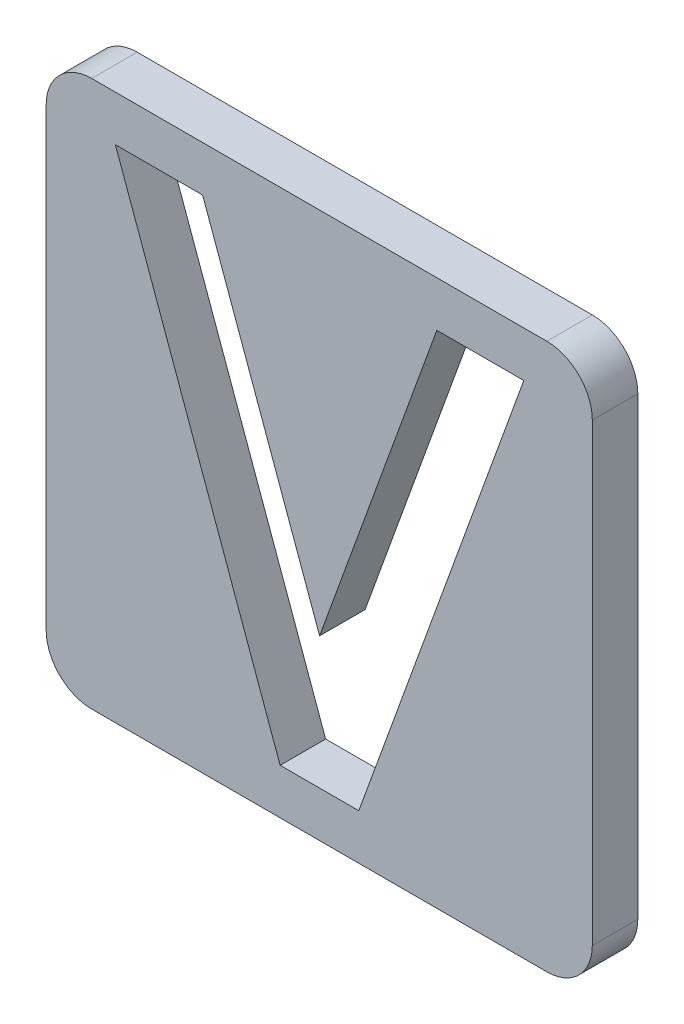
SolidWorks part; units mm, degrees
ref_plane "Front Plane" through (0, 0, 0) normal (0, 0, 1) x (1, 0, 0)
ref_plane "Top Plane" through (0, 0, 0) normal (0, 1, 0) x (1, 0, 0)
ref_plane "Right Plane" through (0, 0, 0) normal (1, 0, 0) x (0, 0, -1)
sketch "Sketch1" plane through (0, 0, 0) normal (0, 0, 1) x (1, 0, 0)
  line L1 (-50, 60) -> (50, 60)
  line L2 (-60, 50) -> (-60, -50)
  line L3 (-50, -60) -> (50, -60)
  line L4 (60, 50) -> (60, -50)
  line L5 (-60, 60) -> (60, -60) construction
  line L6 (-60, -60) -> (60, 60) construction
  arc A0 (-60, -50) -> (-50, -60) centre (-50, -50) ccw
  arc A1 (50, -60) -> (60, -50) centre (50, -50) ccw
  arc A2 (50, 60) -> (60, 50) centre (50, 50) cw
  arc A3 (-50, 60) -> (-60, 50) centre (-50, 50) ccw
  point P0 (0, 0)
  dimension "D3" = 10
  dimension "D1" = 120
  dimension "D2" = 120
extrude "Boss-Extrude1" add sketch "Sketch1" along normal blind 10 contours A3 L2 A0 L3 A1 L4 A2 L1
sketch "Sketch2" plane through (0, 0, 10) normal (0, 0, 1) x (1, 0, 0)
  line L0 (0, 0) -> (0, 40) construction
  line L1 (-50, 50) -> (50, 50) construction
  line L2 (-50, 50) -> (-50, -50) construction
  line L3 (-50, -50) -> (50, -50) construction
  line L4 (50, 50) -> (50, -50) construction
  line L5 (-50, 50) -> (50, -50) construction
  line L6 (-50, -50) -> (50, 50) construction
  line L7 (0, 40) -> (-40, 40) construction
  line L8 (-40, 40) -> (-40, 0) construction
  line L9 (-40, 0) -> (0, 0) construction
  line L11 (0, 20) -> (-20, 20) construction
  line L12 (-20, 40) -> (-20, 20) construction
  circle A0 centre (0, 40) radius 4 construction
  circle A1 centre (0, 20) radius 4 construction
  circle A2 centre (0, 0) radius 4 construction
  circle A3 centre (-20, 20) radius 4 construction
  circle A4 centre (-20, 40) radius 4 construction
  circle A5 centre (-40, 40) radius 4 construction
  circle A6 centre (0, 0) radius 4 construction
  circle A7 centre (20, 0) radius 4 construction
  circle A8 centre (40, 0) radius 4 construction
  circle A9 centre (40, 20) radius 4 construction
  circle A10 centre (40, 40) radius 4 construction
  circle A11 centre (20, 20) radius 4 construction
  circle A12 centre (0, 0) radius 4 construction
  circle A13 centre (0, -20) radius 4 construction
  circle A14 centre (0, -40) radius 4 construction
  circle A15 centre (20, -40) radius 4 construction
  circle A16 centre (40, -40) radius 4 construction
  circle A17 centre (20, -20) radius 4 construction
  circle A18 centre (0, 0) radius 4 construction
  circle A19 centre (-20, 0) radius 4 construction
  circle A20 centre (-40, 0) radius 4 construction
  circle A21 centre (-40, -20) radius 4 construction
  circle A22 centre (-40, -40) radius 4 construction
  circle A23 centre (-20, -20) radius 4 construction
  text T0 "V" font "Century Gothic" height 100
  point P0 (0, 0)
  point P55 (0, 0)
  dimension "D4" = 8
  dimension "D1" = 100
  dimension "D2" = 100
  dimension "D3" = 40
  dimension "D5" = 4
extrude "Cut-Extrude35" cut sketch "Sketch2" against normal blind 10
